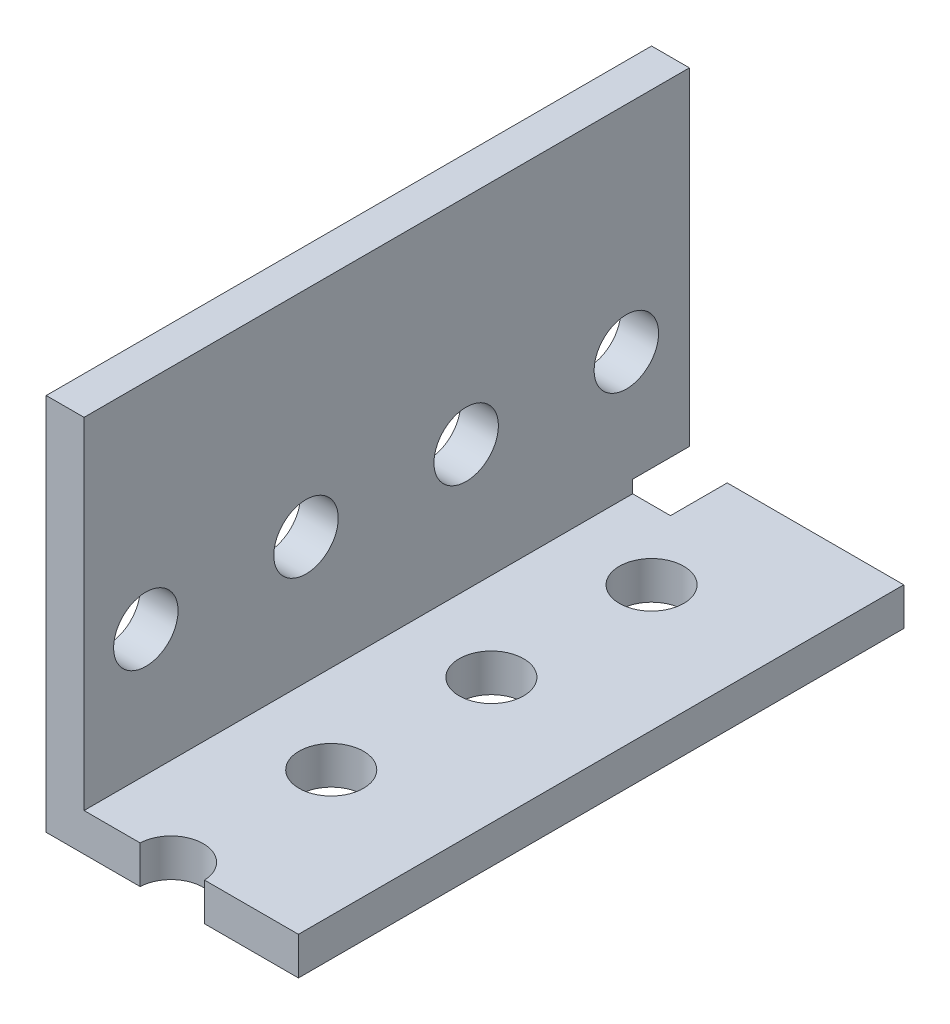
SolidWorks part; units mm, degrees
ref_plane "前视基准面" through (0, 0, 0) normal (0, 0, 1) x (1, 0, 0)
ref_plane "上视基准面" through (0, 0, 0) normal (0, 1, 0) x (1, 0, 0)
ref_plane "右视基准面" through (0, 0, 0) normal (1, 0, 0) x (0, 0, -1)
sketch "草图1" plane through (0, 0, 0) normal (0, 0, 1) x (1, 0, 0)
  line L5 (-1.5, 15) -> (1.5, 15)
  line L6 (-1.5, 15) -> (-1.5, -15)
  line L7 (-1.5, -15) -> (1.5, -15)
  line L8 (1.5, 15) -> (1.5, -15)
  line L9 (-1.5, 15) -> (1.5, -15) construction
  line L10 (-1.5, -15) -> (1.5, 15) construction
  line L11 (-1.5, -15) -> (18.5, -15)
  line L12 (-1.5, -15) -> (-1.5, -12)
  line L13 (-1.5, -12) -> (18.5, -12)
  line L14 (18.5, -15) -> (18.5, -12)
  point P0 (0, 0)
  dimension "D1" = 3
  dimension "D2" = 30
  dimension "D3" = 20
  dimension "D4" = 3
extrude "凸台-拉伸1" add sketch "草图1" along normal blind 48 contours L6 L13 L8 L5 | L13 L6 L7 L8 | L11 L14 L13 L8
sketch "草图2" plane through (0, -12, 0) normal (0, 1, 0) x (1, 0, 0)
  line L0 (18.5, -48) -> (18.5, 0) construction
  line L1 (1.5, 0) -> (18.5, 0) construction
  circle A0 centre (8.5, -10) radius 2.555
  circle A1 centre (8.5, -22.7) radius 2.555
  circle A2 centre (8.5, -35.4) radius 2.555
  circle A3 centre (8.5, -48.1) radius 2.555
  circle A4 centre (8.5, -60.8) radius 2.555
  dimension "D2" = 10
  dimension "D3" = 5.11
  dimension "D1" = 10
  dimension "D5" = 12.7
  dimension "D4" = 5
extrude "切除-拉伸1" cut sketch "草图2" against normal through all
sketch "草图3" plane through (-1.5, 0, 0) normal (-1, 0, 0) x (0, 0, 1)
  line L0 (0, 15) -> (0, -15) construction
  line L1 (48, 15) -> (0, 15) construction
  circle A0 centre (5, -2) radius 2.555
  circle A1 centre (17.7, -2) radius 2.555
  circle A2 centre (30.4, -2) radius 2.555
  circle A3 centre (43.1, -2) radius 2.555
  circle A4 centre (55.8, -2) radius 2.555
  dimension "D1" = 5.11
  dimension "D4" = 12.7
  dimension "D2" = 5
  dimension "D5" = 17
  dimension "D3" = 5
extrude "切除-拉伸2" cut sketch "草图3" against normal through all
ref_plane "基准面1" through (0, 50, 0) normal (0, 1, 0) x (1, 0, 0)
sketch "草图4" plane through (0, 0, 0) normal (0, 0, -1) x (-1, 0, 0)
  line L6 (1.5, -15) -> (-4.5, -15)
  line L9 (1.5, -15) -> (1.5, -11)
  line L10 (1.5, -11) -> (-4.5, -11)
  line L11 (-4.5, -15) -> (-4.5, -11)
  dimension "D1" = 6
  dimension "D2" = 4
extrude "切除-拉伸3" cut sketch "草图4" against normal blind 4.5
